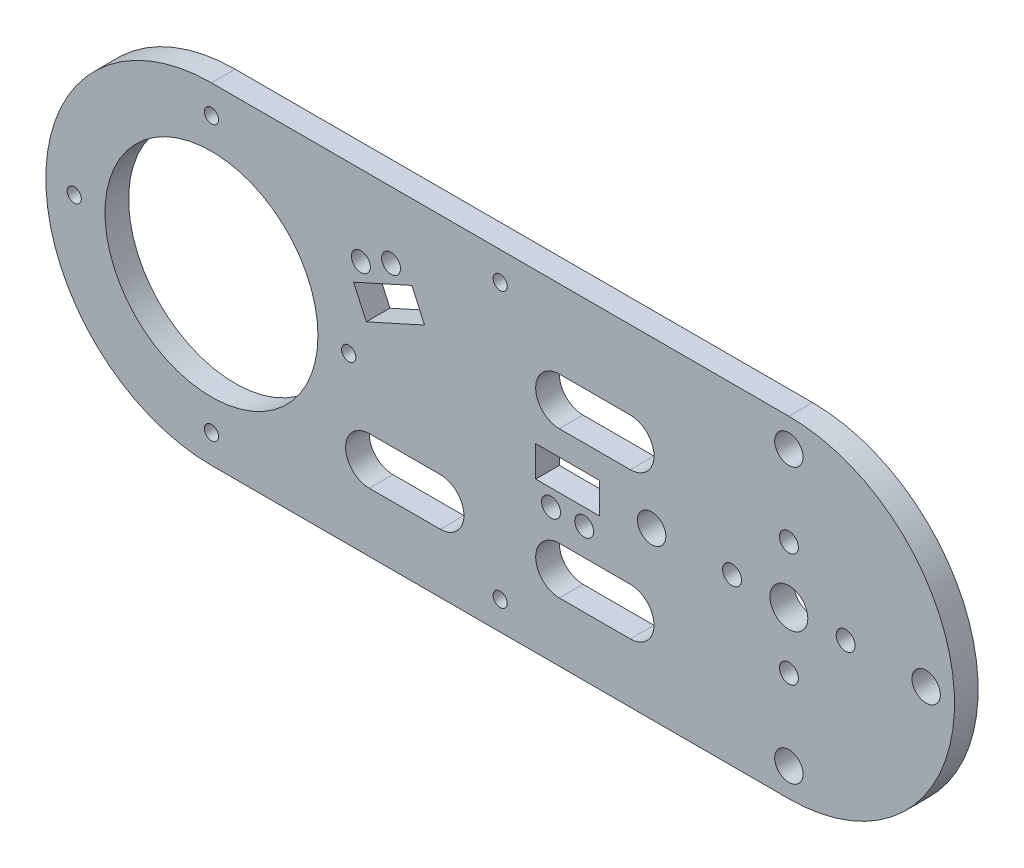
SolidWorks part; units mm, degrees
ref_plane "Front Plane" through (0, 0, 0) normal (0, 0, 1) x (1, 0, 0)
ref_plane "Top Plane" through (0, 0, 0) normal (0, 1, 0) x (1, 0, 0)
ref_plane "Right Plane" through (0, 0, 0) normal (1, 0, 0) x (0, 0, -1)
sketch "Sketch1" plane through (0, 0, 0) normal (0, 0, 1) x (1, 0, 0)
  line L0 (61, 0) -> (-61, 0) construction
  line L1 (12.5, -17.5) -> (12.5, 13.47) construction
  line L2 (61, -35) -> (-61, -35)
  line L3 (61, 35) -> (-61, 35)
  line L17 (7.5, 3.25) -> (7.5, -3.25)
  line L20 (7.5, -3.25) -> (21, -3.25)
  line L23 (21, -3.25) -> (21, 3.25)
  line L24 (21, 3.25) -> (7.5, 3.25)
  line L27 (-27.66, -17.5) -> (-12.66, -17.5) construction
  line L28 (12.5, -17.5) -> (27.5, -17.5) construction
  line L29 (-27.66, -12.5) -> (-12.66, -12.5)
  line L30 (-27.66, -22.5) -> (-12.66, -22.5)
  line L31 (12.5, 13.47) -> (27.5, 13.47) construction
  line L32 (12.5, -12.5) -> (27.5, -12.5)
  line L33 (12.5, -22.5) -> (27.5, -22.5)
  line L35 (12.5, 18.47) -> (27.5, 18.47)
  line L36 (12.5, 8.47) -> (27.5, 8.47)
  line L37 (-61, 0) -> (-30.9578, 13.5583) construction
  line L38 (-30.9578, 13.5583) -> (-28.284, 7.6337)
  line L39 (-28.284, 7.6337) -> (-15.9791, 13.187)
  line L40 (-15.9791, 13.187) -> (-18.6529, 19.1116)
  line L41 (-18.6529, 19.1116) -> (-30.9578, 13.5583)
  arc A0 (61, -35) -> (61, 35) centre (61, 0) ccw
  arc A1 (-61, 35) -> (-61, -35) centre (-61, 0) ccw
  circle A2 centre (61, 0) radius 4
  circle A3 centre (-61, 0) radius 22.5
  circle A4 centre (-61, -29) radius 1.5
  circle A5 centre (-61, 29) radius 1.5
  circle A6 centre (61, 29) radius 3
  circle A7 centre (61, -29) radius 3
  circle A8 centre (0, -29) radius 1.5
  circle A9 centre (0, 29) radius 1.5
  circle A12 centre (-90, 0) radius 1.5
  circle A13 centre (-32, 0) radius 1.5
  circle A16 centre (90, 0) radius 3
  circle A17 centre (32, 0) radius 3
  circle A34 centre (61, 12) radius 2
  circle A35 centre (61, -12) radius 2
  circle A36 centre (49, 0) radius 2
  circle A37 centre (73, 0) radius 2
  arc A38 (-27.66, -12.5) -> (-27.66, -22.5) centre (-27.66, -17.5) ccw
  arc A39 (-12.66, -22.5) -> (-12.66, -12.5) centre (-12.66, -17.5) ccw
  arc A40 (12.5, -12.5) -> (12.5, -22.5) centre (12.5, -17.5) ccw
  arc A41 (27.5, -22.5) -> (27.5, -12.5) centre (27.5, -17.5) ccw
  arc A42 (12.5, 18.47) -> (12.5, 8.47) centre (12.5, 13.47) ccw
  arc A43 (27.5, 8.47) -> (27.5, 18.47) centre (27.5, 13.47) ccw
  circle A44 centre (10.75, -6.75) radius 2
  circle A45 centre (17.75, -6.75) radius 2
  circle A46 centre (-23.0549, 20.9648) radius 2
  circle A47 centre (-29.4352, 18.0853) radius 2
  point P5 (0, 0)
  point P27 (-61, 0)
  point P28 (7.5, 0)
  point P32 (-61, 0)
  point P53 (-20.16, -17.5)
  point P59 (20, -17.5)
  point P66 (20, 13.47)
  point P74 (14.25, -6.75)
  point P83 (-26.2451, 19.5251)
  dimension "D1" = 8
  dimension "D3" = 6
  dimension "D4" = 3
  dimension "D5" = 6
  dimension "D6" = 3
  dimension "D8" = 6
  dimension "D9" = 6
  dimension "D12" = 3
  dimension "D13" = 3
  dimension "D14" = 70
  dimension "D15" = 12
  dimension "D16" = 12
  dimension "D19" = 3
  dimension "D20" = 3
  dimension "D24" = 29
  dimension "D25" = 6
  dimension "D26" = 6
  dimension "D27" = 4
  dimension "D28" = 4
  dimension "D29" = 4
  dimension "D30" = 29
  dimension "D31" = 13.5
  dimension "D32" = 6.5
  dimension "D33" = 68.5
  dimension "D34" = 33.34
  dimension "D45" = 45
  dimension "D22" = 4
  dimension "D41" = 4
  dimension "D42" = 4
  dimension "D46" = 6
  dimension "D7" = 122
  dimension "D10" = 6
  dimension "D11" = 6
  dimension "D17" = 12
  dimension "D18" = 58
  dimension "D21" = 12
  dimension "D23" = 29
  dimension "D35" = 15
  dimension "D36" = 10
  dimension "D37" = 73.5
  dimension "D38" = 15
  dimension "D39" = 10
  dimension "D40" = 30.97
  dimension "D43" = 7
  dimension "D44" = 32.96
  dimension "D47" = 6
extrude "Boss-Extrude1" add sketch "Sketch1" along normal blind 5
